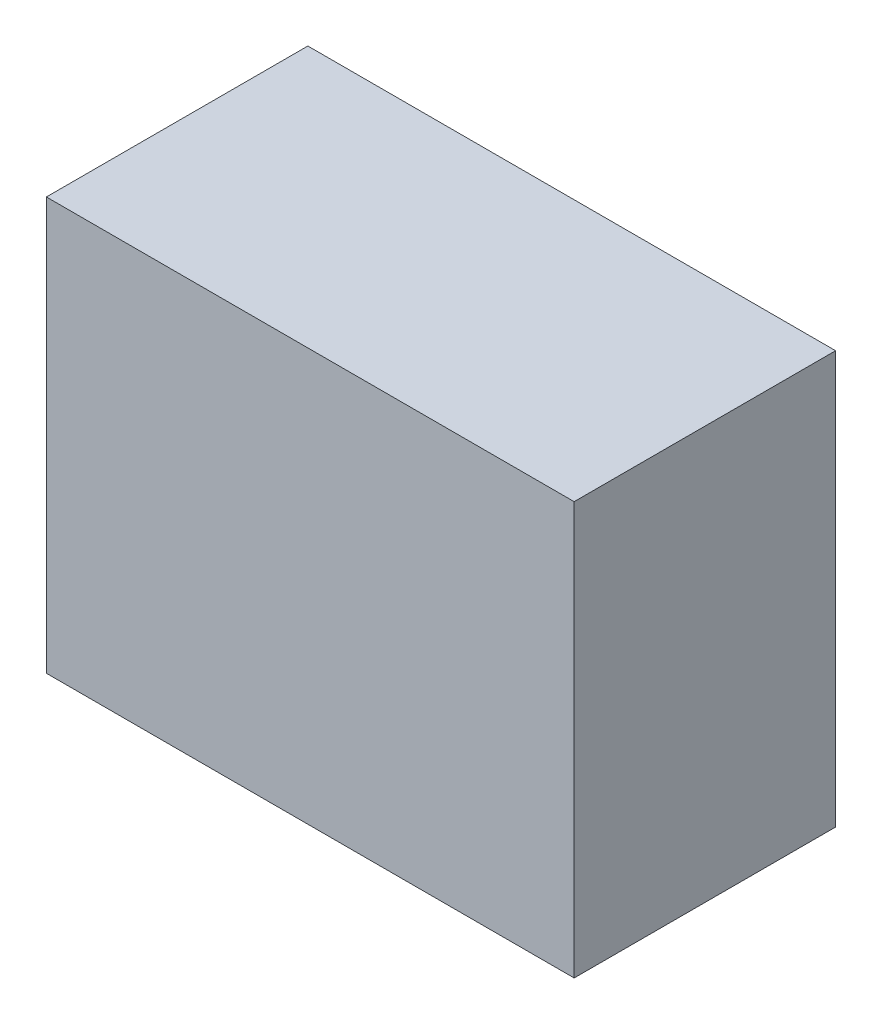
SolidWorks part; units mm, degrees
ref_plane "Front Plane" through (0, 0, 0) normal (0, 0, 1) x (1, 0, 0)
ref_plane "Top Plane" through (0, 0, 0) normal (0, 1, 0) x (1, 0, 0)
ref_plane "Right Plane" through (0, 0, 0) normal (1, 0, 0) x (0, 0, -1)
sketch "Sketch1" plane through (0, 0, 0) normal (0, 0, 1) x (1, 0, 0)
  line L0 (-0.4, -0.4) -> (-0.4, 35.4)
  line L1 (0, 0) -> (45, 0)
  line L2 (0, 0) -> (0, 35)
  line L3 (0, 35) -> (45, 35)
  line L4 (45, 0) -> (45, 35)
  line L5 (-0.4, 35.4) -> (45.4, 35.4)
  line L6 (45.4, -0.4) -> (45.4, 35.4)
  line L7 (-0.4, -0.4) -> (45.4, -0.4)
  dimension "D1" = 45
  dimension "D2" = 35
  dimension "D3" = 0.4
extrude "Boss-Extrude1" add sketch "Sketch1" along normal blind 22.14
sketch "Sketch2" plane through (0, 0, 22.14) normal (0, 0, 1) x (1, 0, 0)
  line L1 (-0.4, -0.4) -> (45.4, -0.4)
  line L2 (-0.4, -0.4) -> (-0.4, 35.4)
  line L3 (-0.4, 35.4) -> (45.4, 35.4)
  line L4 (45.4, -0.4) -> (45.4, 35.4)
extrude "Boss-Extrude2" add sketch "Sketch2" along normal blind 0.55
